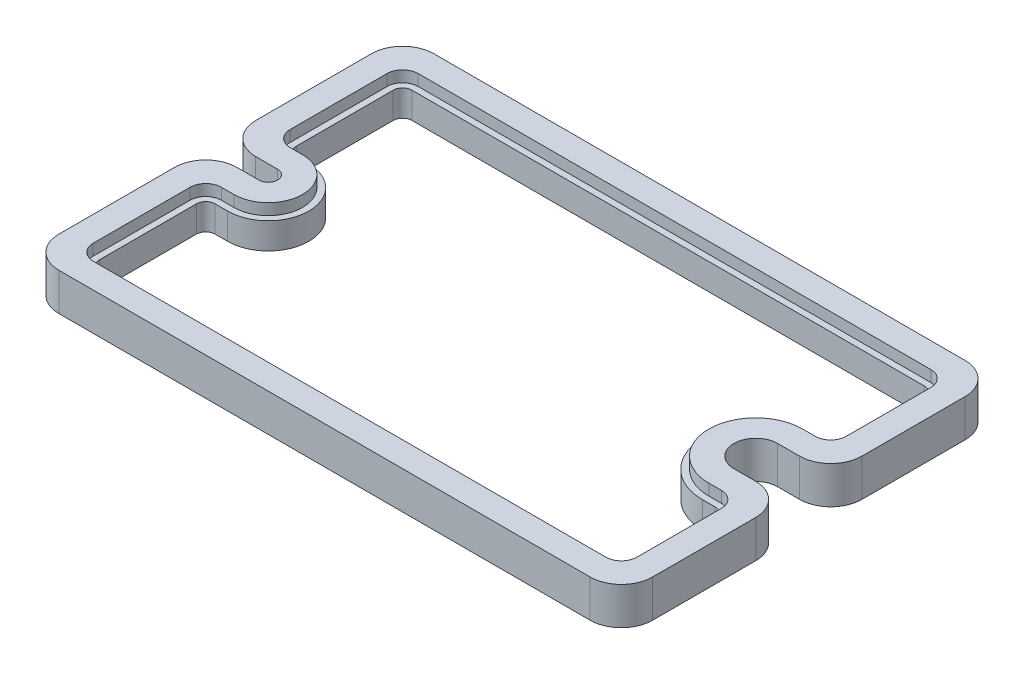
SolidWorks part; units mm, degrees
ref_plane "Front Plane" through (0, 0, 0) normal (0, 0, 1) x (1, 0, 0)
ref_plane "Top Plane" through (0, 0, 0) normal (0, 1, 0) x (1, 0, 0)
ref_plane "Right Plane" through (0, 0, 0) normal (1, 0, 0) x (0, 0, -1)
sketch "Sketch1" plane through (0, 0, 0) normal (0, 1, 0) x (1, 0, 0)
  line L0 (47.5, 0) -> (47.5, 60) construction
  line L1 (0, 0) -> (95, 0)
  line L2 (0, 0) -> (0, 60)
  line L3 (0, 60) -> (95, 60)
  line L4 (95, 0) -> (95, 60)
  line L5 (47.5, 3.5) -> (78, 3.5) construction
  line L6 (47.5, 3.5) -> (17, 3.5) construction
  line L7 (47.5, 21) -> (78, 21) construction
  line L8 (47.5, 21) -> (17, 21) construction
  line L9 (47.5, 38.5) -> (78, 38.5) construction
  line L10 (47.5, 38.5) -> (17, 38.5) construction
  line L11 (47.5, 56) -> (78, 56) construction
  line L12 (47.5, 56) -> (17, 56) construction
  line L13 (17, 3.5) -> (17, 21) construction
  line L14 (17, 21) -> (17, 38.5) construction
  line L15 (17, 38.5) -> (17, 56) construction
  dimension "D1" = 95
  dimension "D2" = 60
  dimension "D3" = 30.5
  dimension "D4" = 17.5
  dimension "D5" = 3.5
extrude "Boss-Extrude1" add sketch "Sketch1" along normal blind 6
sketch "Sketch6" plane through (0, 0, 0) normal (0, -1, 0) x (1, 0, 0)
  line L0 (0, -30) -> (95, -30) construction
  line L1 (0, -60) -> (0, 0) construction
  line L2 (95, 0) -> (95, -60) construction
  line L3 (95, -30) -> (86.5, -30) construction
  line L4 (0, -30) -> (8.5, -30) construction
  line L5 (10, -30) -> (83, -30) construction
  circle A0 centre (86.5, -30) radius 3.5
  circle A2 centre (8.5, -30) radius 1.5
  dimension "D2" = 8.5
  dimension "D3" = 3
  dimension "D4" = 7
  dimension "D5" = 73
  dimension "D1" = 8.5
extrude "Cut-Extrude3" cut sketch "Sketch6" against normal through all
sketch "Sketch2" plane through (0, 6, 0) normal (0, 1, 0) x (-1, 0, 0)
  line L5 (0, 0) -> (-95, 0) construction
  line L6 (-95, -60) -> (0, -60) construction
  line L7 (0, -60) -> (0, 0) construction
  line L8 (-95, 0) -> (-95, -60) construction
  line L9 (-8.5, -36.5) -> (-5, -36.5)
  line L10 (-8.5, -23.5) -> (-5, -23.5)
  line L11 (-86.5, -38.5) -> (-90, -38.5)
  line L12 (-86.5, -21.5) -> (-90, -21.5)
  line L13 (-5, -5) -> (-90, -5)
  line L14 (-90, -5) -> (-90, -21.5)
  line L15 (-90, -55) -> (-5, -55)
  line L16 (-5, -55) -> (-5, -36.5)
  line L17 (-90, -38.5) -> (-90, -55)
  line L20 (-5, -23.5) -> (-5, -5)
  arc A0 (-8.5, -23.5) -> (-8.5, -36.5) centre (-8.5, -30) ccw
  arc A1 (-86.5, -38.5) -> (-86.5, -21.5) centre (-86.5, -30) ccw
  circle A2 centre (-86.5, -30) radius 3.5 construction
  circle A3 centre (-8.5, -30) radius 1.5 construction
  dimension "D5" = 5
  dimension "D6" = 5
  dimension "D1" = 5
  dimension "D2" = 5
  dimension "D3" = 5
  dimension "D4" = 5
  dimension "D7" = 5
extrude "Cut-Extrude1" cut sketch "Sketch2" against normal through all
fillet "Fillet3" radius 1.5 1 edges at (90, 3, -55)
sketch "Sketch7" plane through (0, 6, 0) normal (0, 1, 0) x (-1, 0, 0)
  line L0 (0, -60) -> (0, 0) construction
  line L1 (0, -31.5) -> (-8.5, -31.5)
  line L2 (0, -31.5) -> (0, -28.5)
  line L3 (0, -28.5) -> (-8.5, -28.5)
  line L4 (-8.5, -31.5) -> (-8.5, -28.5)
  line L5 (-95, 0) -> (-95, -60) construction
  line L6 (-95, -33.5) -> (-86.5, -33.5)
  line L7 (-95, -33.5) -> (-95, -26.5)
  line L8 (-95, -26.5) -> (-86.5, -26.5)
  line L9 (-86.5, -33.5) -> (-86.5, -26.5)
  line L10 (0, -60) -> (0, -30) construction
  line L11 (0, 0) -> (0, -30) construction
  line L12 (-95, -30) -> (-95, 0) construction
  line L15 (-95, -60) -> (-95, -30) construction
  circle A0 centre (-86.5, -30) radius 3.5 construction
  dimension "D1" = 3
  dimension "D2" = 7
extrude "Cut-Extrude4" cut sketch "Sketch7" against normal through all
fillet "Fillet4" radius 5 8 edges at (95, 3, -33.5) (0, 3, 0) (0, 3, -28.5) (0, 3, -31.5) (0, 3, -60) (95, 3, -60) (95, 3, -26.5) (95, 3, 0)
fillet "Fillet5" radius 1.5 7 edges at (90, 3, -38.5) (90, 3, -5) (90, 3, -21.5) (5, 3, -5) (5, 3, -36.5) (5, 3, -23.5) (5, 3, -55)
sketch "Sketch9" plane through (0, 6, 0) normal (0, 1, 0) x (1, 0, 0)
  line L28 (6.5, 4) -> (88.5, 4)
  line L29 (91, 6.5) -> (91, 20)
  line L30 (88.5, 22.5) -> (86.5, 22.5)
  line L31 (86.5, 37.5) -> (88.5, 37.5)
  line L32 (91, 40) -> (91, 53.5)
  line L33 (88.5, 56) -> (6.5, 56)
  line L34 (4, 53.5) -> (4, 38)
  line L35 (6.5, 35.5) -> (8.5, 35.5)
  line L36 (8.5, 24.5) -> (6.5, 24.5)
  line L37 (4, 22) -> (4, 6.5)
  line L38 (6.5, 4) -> (88.5, 4)
  line L39 (91, 6.5) -> (91, 20)
  line L40 (88.5, 22.5) -> (86.5, 22.5)
  line L41 (86.5, 37.5) -> (88.5, 37.5)
  line L42 (91, 40) -> (91, 53.5)
  line L43 (88.5, 56) -> (6.5, 56)
  line L44 (4, 53.5) -> (4, 38)
  line L45 (6.5, 35.5) -> (8.5, 35.5)
  line L46 (8.5, 24.5) -> (6.5, 24.5)
  line L47 (4, 22) -> (4, 6.5)
  arc A20 (4, 6.5) -> (6.5, 4) centre (6.5, 6.5) ccw
  arc A21 (88.5, 4) -> (91, 6.5) centre (88.5, 6.5) ccw
  arc A22 (91, 20) -> (88.5, 22.5) centre (88.5, 20) ccw
  arc A23 (86.5, 37.5) -> (86.5, 22.5) centre (86.5, 30) ccw
  arc A24 (88.5, 37.5) -> (91, 40) centre (88.5, 40) ccw
  arc A25 (91, 53.5) -> (88.5, 56) centre (88.5, 53.5) ccw
  arc A26 (6.5, 56) -> (4, 53.5) centre (6.5, 53.5) ccw
  arc A27 (4, 38) -> (6.5, 35.5) centre (6.5, 38) ccw
  arc A28 (8.5, 24.5) -> (8.5, 35.5) centre (8.5, 30) ccw
  arc A29 (6.5, 24.5) -> (4, 22) centre (6.5, 22) ccw
  arc A30 (4, 6.5) -> (6.5, 4) centre (6.5, 6.5) ccw
  arc A31 (88.5, 4) -> (91, 6.5) centre (88.5, 6.5) ccw
  arc A32 (91, 20) -> (88.5, 22.5) centre (88.5, 20) ccw
  arc A33 (86.5, 37.5) -> (86.5, 22.5) centre (86.5, 30) ccw
  arc A34 (88.5, 37.5) -> (91, 40) centre (88.5, 40) ccw
  arc A35 (91, 53.5) -> (88.5, 56) centre (88.5, 53.5) ccw
  arc A36 (6.5, 56) -> (4, 53.5) centre (6.5, 53.5) ccw
  arc A37 (4, 38) -> (6.5, 35.5) centre (6.5, 38) ccw
  arc A38 (8.5, 24.5) -> (8.5, 35.5) centre (8.5, 30) ccw
  arc A39 (6.5, 24.5) -> (4, 22) centre (6.5, 22) ccw
  dimension "D2" = 1
extrude "Cut-Extrude5" cut sketch "Sketch9" against normal blind 1.8
